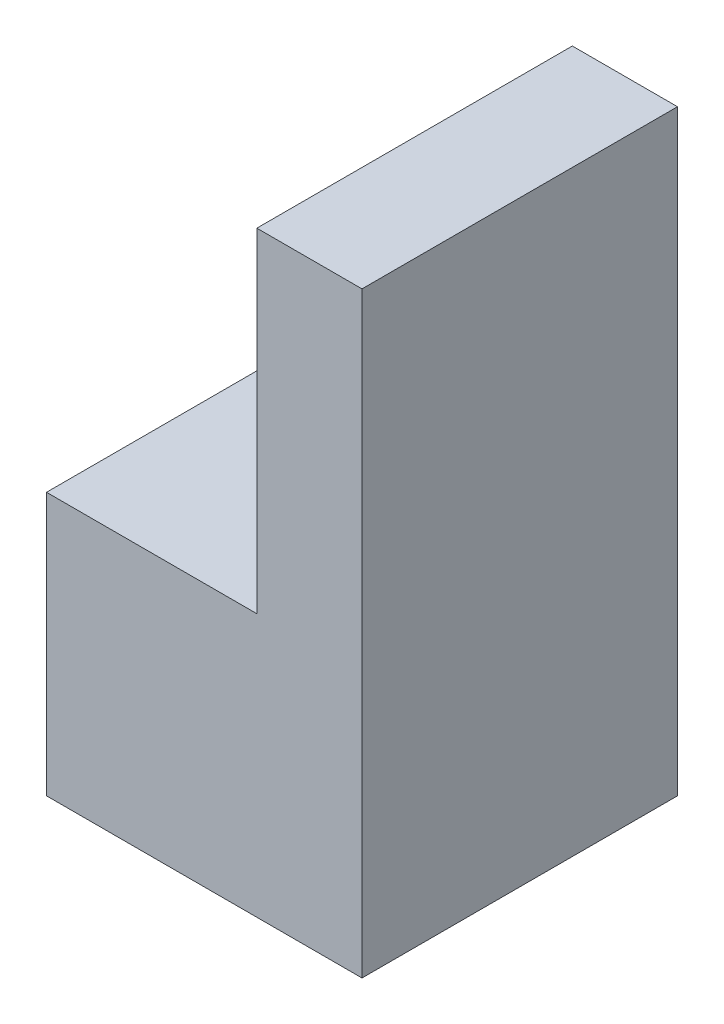
SolidWorks part; units mm, degrees
ref_plane "Front" through (0, 0, 0) normal (0, 0, 1) x (1, 0, 0)
ref_plane "Top" through (0, 0, 0) normal (0, 1, 0) x (1, 0, 0)
ref_plane "Right" through (0, 0, 0) normal (1, 0, 0) x (0, 0, -1)
sketch "Sketch1" plane through (0, 0, 0) normal (0, 1, 0) x (1, 0, 0)
  line L1 (0, 0) -> (24, 0)
  line L2 (0, 0) -> (0, 24)
  line L3 (0, 24) -> (24, 24)
  line L4 (24, 0) -> (24, 24)
  dimension "D1" = 24
  dimension "D2" = 24
extrude "Boss-Extrude1" add sketch "Sketch1" along normal blind 20
sketch "Sketch2" plane through (0, 20, 0) normal (0, 1, 0) x (1, 0, 0)
  line L0 (0, 0) -> (24, 0) construction
  line L1 (24, 24) -> (16, 24)
  line L2 (24, 24) -> (24, 0)
  line L3 (24, 0) -> (16, 0)
  line L4 (16, 24) -> (16, 0)
  dimension "D1" = 8
extrude "Boss-Extrude2" add sketch "Sketch2" along normal blind 25.4
sketch "Sketch3" plane through (0, 0, 0) normal (0, -1, 0) x (-1, 0, 0)
  line L0 (-4, 24) -> (-4, 16)
  line L1 (-24, 24) -> (0, 24) construction
  line L2 (-4, 16) -> (-4, 8)
  line L3 (0, 24) -> (0, 0) construction
  circle A0 centre (-4, 16) radius 1.65
  circle A1 centre (-4, 8) radius 1.65
  circle A2 centre (-12, 8) radius 1.65
  circle A3 centre (-12, 16) radius 1.65
  circle A4 centre (-20, 8) radius 1.65
  circle A5 centre (-20, 16) radius 1.65
  dimension "D4" = 3
  dimension "D1" = 4
  dimension "D2" = 8
  dimension "D3" = 8
extrude "Cut-Extrude1" cut sketch "Sketch3" against normal blind 15
